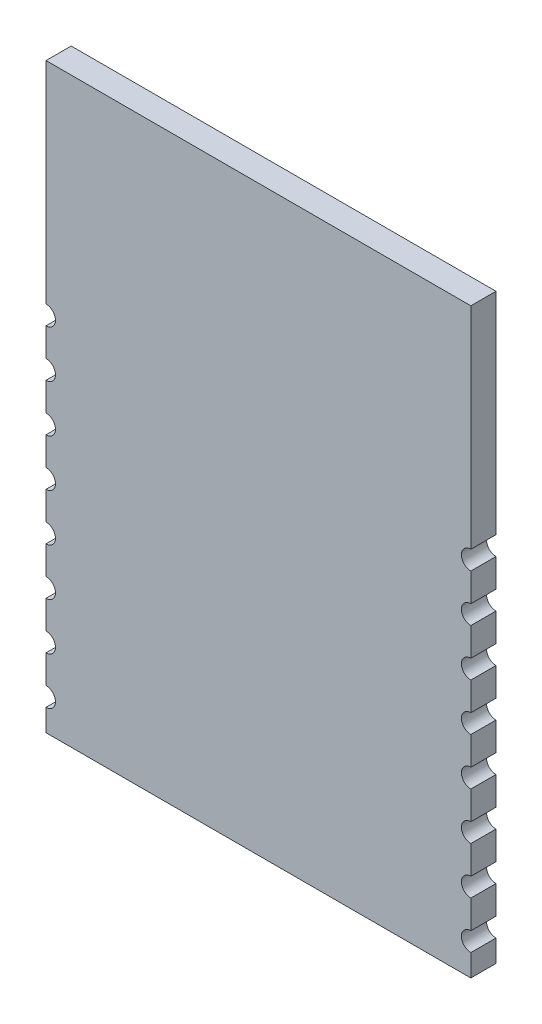
SolidWorks part; units mm, degrees
ref_plane "Plano frontal" through (0, 0, 0) normal (0, 0, 1) x (1, 0, 0)
ref_plane "Plano superior" through (0, 0, 0) normal (0, 1, 0) x (1, 0, 0)
ref_plane "Plano direito" through (0, 0, 0) normal (1, 0, 0) x (0, 0, -1)
sketch "Esboço1" plane through (0, 0, 0) normal (0, 0, 1) x (1, 0, 0)
  line L1 (0, 18.5) -> (13.5, 18.5)
  line L2 (0, 18.5) -> (0, 0)
  line L3 (0, 0) -> (13.5, 0)
  line L4 (13.5, 18.5) -> (13.5, 0)
  point P4 (0, 0)
  dimension "D1" = 18.5
  dimension "D2" = 13.5
extrude "Ressalto-extrusão1" add sketch "Esboço1" along normal blind 0.8
sketch "Esboço2" plane through (0, 0, 0.8) normal (0, 0, 1) x (1, 0, 0)
  line L0 (13.5, 0) -> (13.5, 18.5) construction
  line L1 (0, 0) -> (13.5, 0) construction
  circle A0 centre (13.5, 1) radius 0.3
  dimension "D1" = 0.6
  dimension "D2" = 1
extrude "Corte-extrusão1" cut sketch "Esboço2" against normal through all
pattern_linear "Padrão linear1" count 8 spacing 1.5 along (0, 1, 0) of "Corte-extrusão1"
ref_plane "Plano1" through (6.75, 0, 0) normal (-1, 0, 0) x (0, 0, 1)
mirror "Espelhar1" about plane through (6.75, 0, 0) normal (-1, 0, 0) of "Padrão linear1", "Corte-extrusão1"
